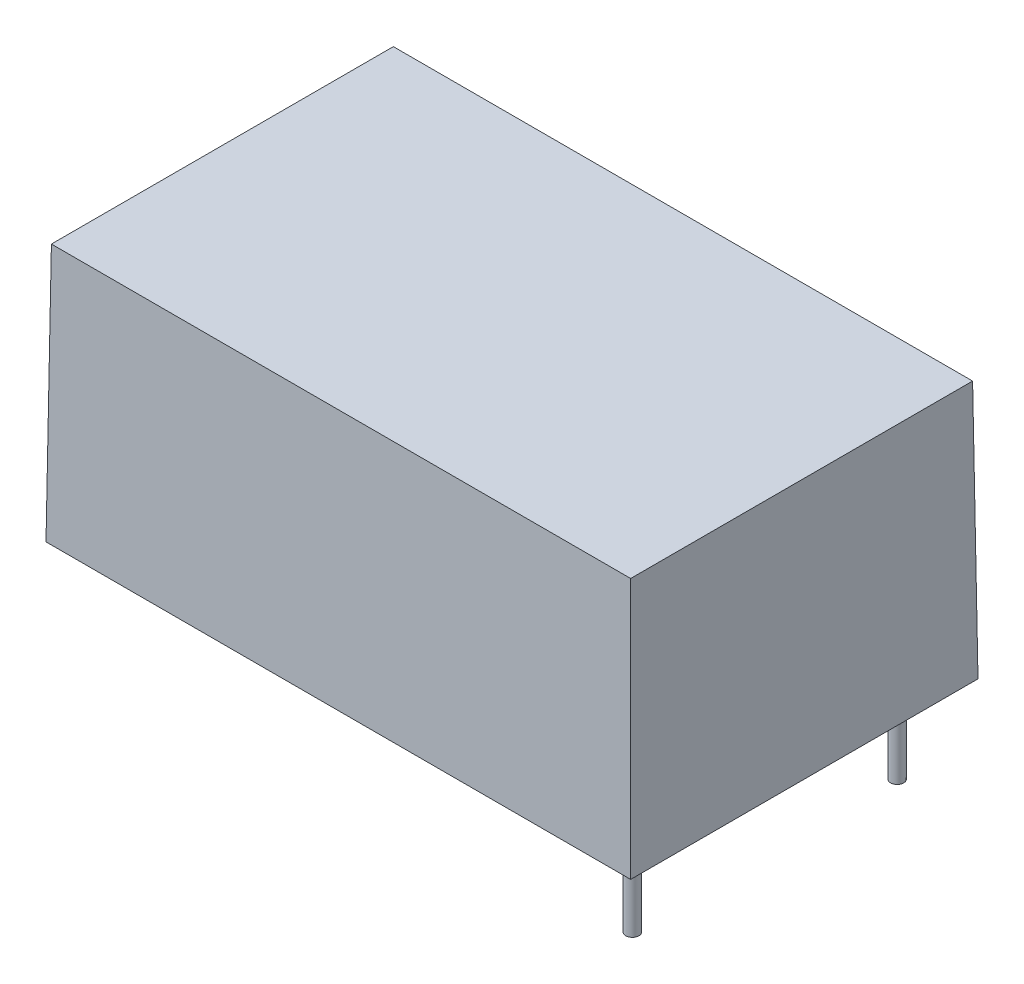
SolidWorks part; units mm, degrees
ref_plane "Front Plane" through (0, 0, 0) normal (0, 0, 1) x (1, 0, 0)
ref_plane "Top Plane" through (0, 0, 0) normal (0, 1, 0) x (1, 0, 0)
ref_plane "Right Plane" through (0, 0, 0) normal (1, 0, 0) x (0, 0, -1)
sketch "Sketch1" plane through (0, 0, 0) normal (0, 1, 0) x (1, 0, 0)
  line L0 (-17, -10.1) -> (17, 10.1) construction
  line L1 (-17, 10.1) -> (17, 10.1)
  line L2 (-17, 10.1) -> (-17, -10.1)
  line L3 (-17, -10.1) -> (17, -10.1)
  line L4 (17, 10.1) -> (17, -10.1)
  point P4 (0, 0)
  dimension "D1" = 20.2
  dimension "D2" = 34
extrude "Boss-Extrude1" add sketch "Sketch1" along normal blind 15 draft 0.6
sketch "Sketch2" plane through (0, 0, 0) normal (0, -1, 0) x (1, 0, 0)
  line L0 (-14.7, 10.1) -> (-14.7, -10.1) construction
  line L1 (-17, 10.1) -> (17, 10.1) construction
  line L2 (17, -10.1) -> (-17, -10.1) construction
  line L3 (14.7, 10.1) -> (14.7, -10.1) construction
  line L4 (-17, 0) -> (17, 0) construction
  line L5 (-17, -10.1) -> (-17, 10.1) construction
  line L6 (17, 10.1) -> (17, -10.1) construction
  line L7 (-14.7, -10.1) -> (14.7, 10.1) construction
  line L8 (0, 10.1) -> (0, -10.1) construction
  circle A0 centre (-14.7, 2.5) radius 0.381
  circle A1 centre (14.7, 7.7) radius 0.381
  circle A2 centre (14.7, -7.7) radius 0.381
  circle A3 centre (-14.7, -2.5) radius 0.381
  point P4 (0, 0)
  dimension "D1" = 0.762
  dimension "D2" = 15.4
  dimension "D3" = 5
  dimension "D4" = 29.4
extrude "Boss-Extrude2" add sketch "Sketch2" along normal blind 5
